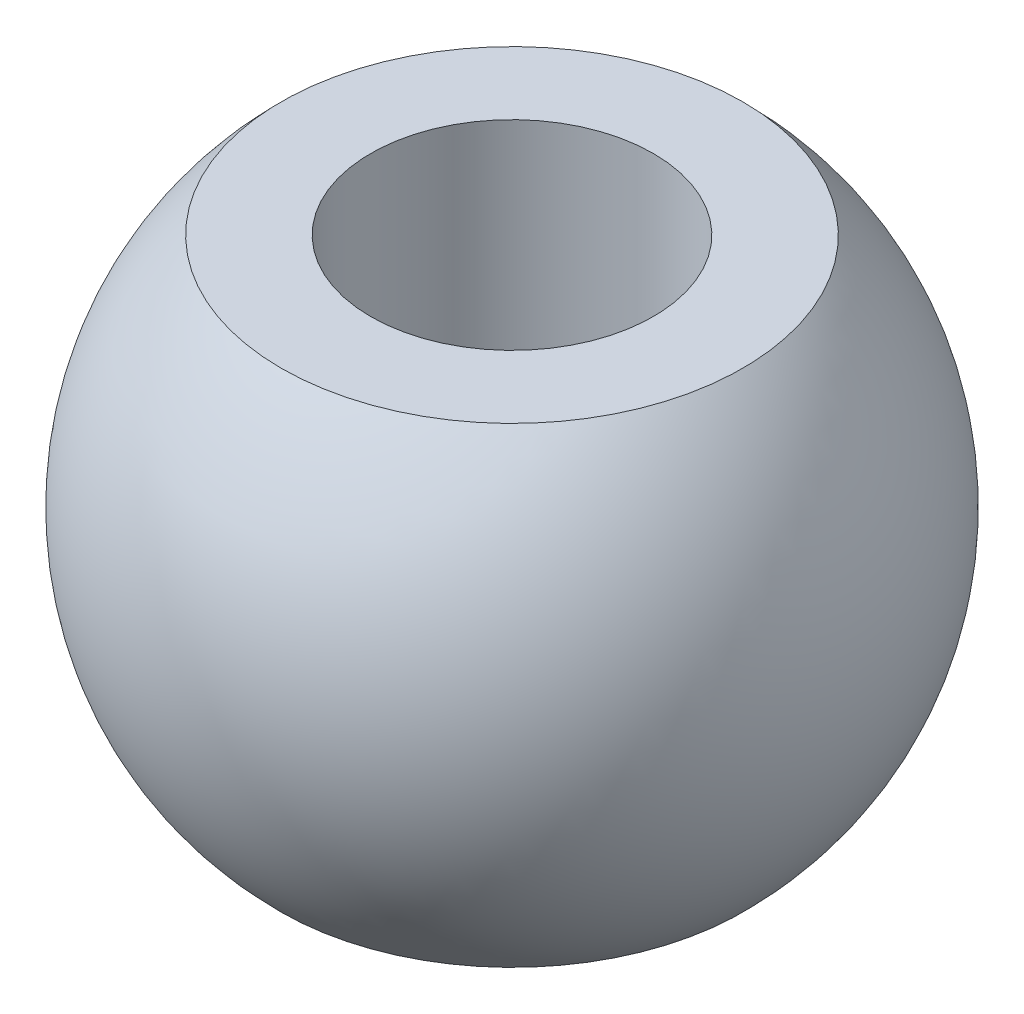
SolidWorks part; units mm, degrees
ref_plane "Front Plane" through (0, 0, 0) normal (0, 0, 1) x (1, 0, 0)
ref_plane "Top Plane" through (0, 0, 0) normal (0, 1, 0) x (1, 0, 0)
ref_plane "Right Plane" through (0, 0, 0) normal (1, 0, 0) x (0, 0, -1)
sketch "Sketch2" plane through (0, 0, 0) normal (0, 1, 0) x (1, 0, 0)
  circle A0 centre (0, 0) radius 3.5
  dimension "D1" = 7
sketch "Sketch3" plane through (0, 0, 0) normal (1, 0, 0) x (0, 0, -1)
  line L0 (1.5, 2.5) -> (2.4495, 2.5)
  line L1 (1.5, -2.5) -> (2.4495, -2.5)
  line L2 (1.5, 2.5) -> (1.5, -2.5)
  arc A0 (2.4495, -2.5) -> (2.4495, 2.5) centre (0, 0) ccw
  dimension "D1" = 7
  dimension "D2" = 1.5
  dimension "D3" = 2.5
  dimension "D4" = 2.5
sweep "Sweep1" add profiles "Sketch3" path "Sketch2"
